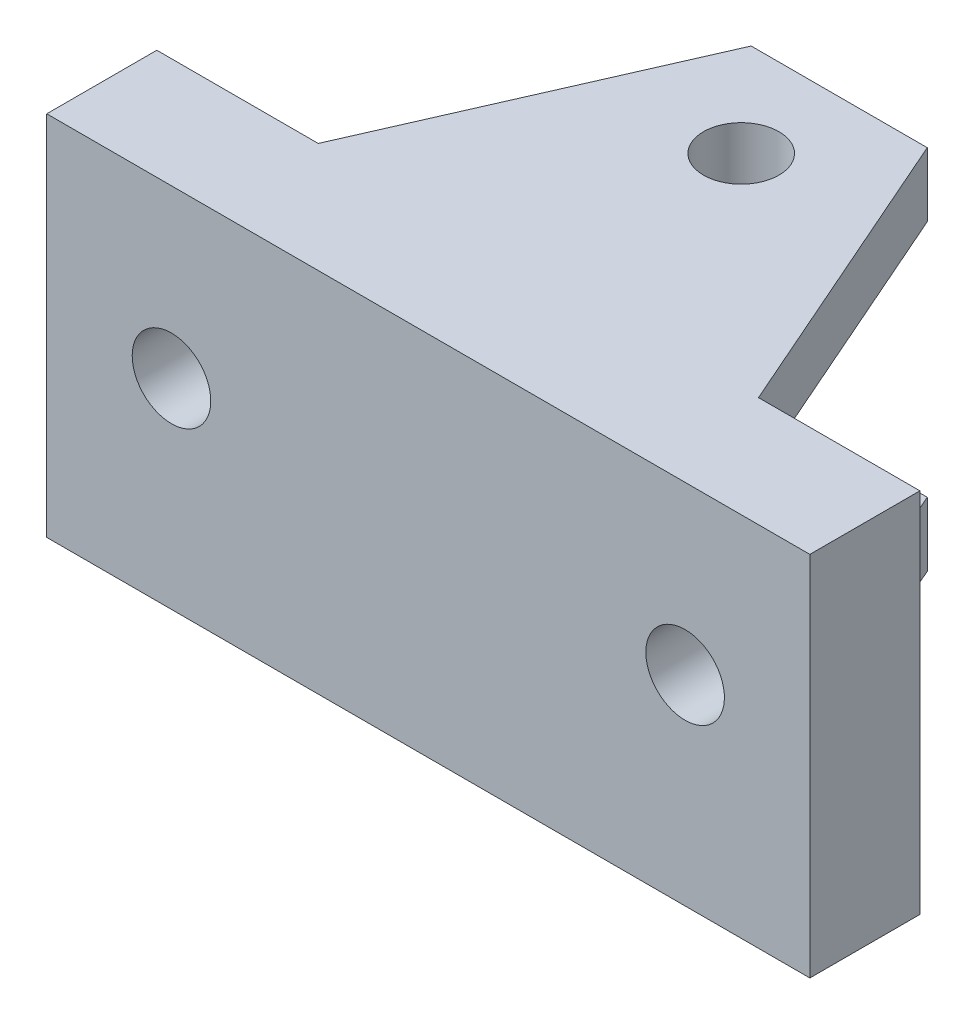
SolidWorks part; units mm, degrees
material "Custom Plastic"
ref_plane "X-Y Datum" through (0, 0, 0) normal (0, 0, 1) x (1, 0, 0)
ref_plane "X-Z Datum" through (0, 0, 0) normal (0, 1, 0) x (1, 0, 0)
ref_plane "Y-Z Datum" through (0, 0, 0) normal (1, 0, 0) x (0, 0, -1)
sketch "Sketch1" plane through (0, 0, 0) normal (1, 0, 0) x (0, 0, -1)
  line L0 (0, 8.7126) -> (0, 40.4626)
  line L1 (0, 40.4626) -> (39.7797, 40.4626)
  line L2 (39.7797, 40.4626) -> (39.7797, 34.9127)
  line L3 (39.7797, 34.9127) -> (9.525, 34.9127)
  line L4 (9.525, 34.9127) -> (9.525, 14.2625)
  line L5 (9.525, 14.2625) -> (39.7797, 14.2625)
  line L6 (39.7797, 14.2625) -> (39.7797, 8.7126)
  line L7 (39.7797, 8.7126) -> (0, 8.7126)
  line L8 (29.6197, 40.4626) -> (29.6197, 8.7126) construction
  line L9 (0, 26.0299) -> (9.525, 26.0299) construction
  line L10 (0, 22.0299) -> (0, 30.0299) construction
  circle A0 centre (29.6197, 24.5876) radius 10.3251 construction
  dimension "D5" = 20.6502
  dimension "D1" = 20.6502
  dimension "D2" = 31.75
  dimension "D3" = 10.16
  dimension "D4" = 9.525
extrude "Boss-Extrude1" add sketch "Sketch1" along normal blind 76.2
sketch "Sketch2" plane through (0, 0, -9.525) normal (0, 0, -1) x (-1, 0, 0)
  line L0 (-38.1, 34.9127) -> (-38.1, 14.2625) construction
  line L1 (-76.2, 34.9127) -> (0, 34.9127) construction
  line L2 (-76.2, 14.2625) -> (0, 14.2625) construction
  line L3 (-60.325, 26.0299) -> (-15.875, 26.0299) construction
  circle A0 centre (-60.325, 26.0299) radius 3.4
  circle A1 centre (-15.875, 26.0299) radius 3.4
  point P8 (-38.1, 26.0299)
  dimension "D2" = 6.8
  dimension "D1" = 44.45
extrude "Cut-Extrude1" cut sketch "Sketch2" against normal up to surface (9.525 mm away) up to face at (38.1, 24.5876, 0)
sketch "Sketch3" plane through (0, 40.4626, 0) normal (0, 1, 0) x (1, 0, 0)
  line L0 (76.2, 39.7797) -> (0, 39.7797) construction
  line L1 (30.48, 35.56) -> (19.05, 9.525)
  line L2 (45.72, 35.56) -> (57.15, 9.525)
  line L3 (30.48, 35.56) -> (45.72, 35.56)
  line L4 (0, 39.7797) -> (0, 9.525)
  line L5 (0, 0) -> (0, 39.7797) construction
  line L6 (0, 9.525) -> (19.05, 9.525)
  line L7 (0, 39.7797) -> (76.2, 39.7797)
  line L8 (76.2, 39.7797) -> (76.2, 9.525)
  line L9 (76.2, 39.7797) -> (76.2, 0) construction
  line L10 (76.2, 9.525) -> (57.15, 9.525)
  line L12 (76.2, 0) -> (0, 0) construction
  circle A0 centre (38.1, 27.0797) radius 3.2639
  point P4 (38.1, 39.7797)
  dimension "D1" = 6.5278
  dimension "D2" = 12.7
  dimension "D3" = 15.24
  dimension "D4" = 35.56
  dimension "D5" = 19.05
extrude "Cut-Extrude2" cut sketch "Sketch3" against normal up to surface (31.75 mm away) up to face at (38.1, 8.7126, -19.8899)
sketch "Sketch4" plane through (0, 0, -9.525) normal (0, 0, -1) x (-1, 0, 0)
  line L0 (0, 40.4626) -> (-19.05, 40.4626) construction
  line L1 (0, 8.7126) -> (-5.08, 8.7126)
  line L2 (0, 8.7126) -> (0, 40.4626)
  line L3 (0, 40.4626) -> (-5.08, 40.4626)
  line L4 (-5.08, 8.7126) -> (-5.08, 40.4626)
  line L5 (-57.15, 40.4626) -> (-76.2, 40.4626) construction
  line L6 (-76.2, 8.7126) -> (-71.12, 8.7126)
  line L7 (-76.2, 8.7126) -> (-76.2, 40.4626)
  line L8 (-76.2, 40.4626) -> (-71.12, 40.4626)
  line L9 (-71.12, 8.7126) -> (-71.12, 40.4626)
  dimension "D1" = 5.08
extrude "Cut-Extrude3" cut sketch "Sketch4" against normal up to surface (9.525 mm away) up to face at (60.325, 29.4299, 0)
